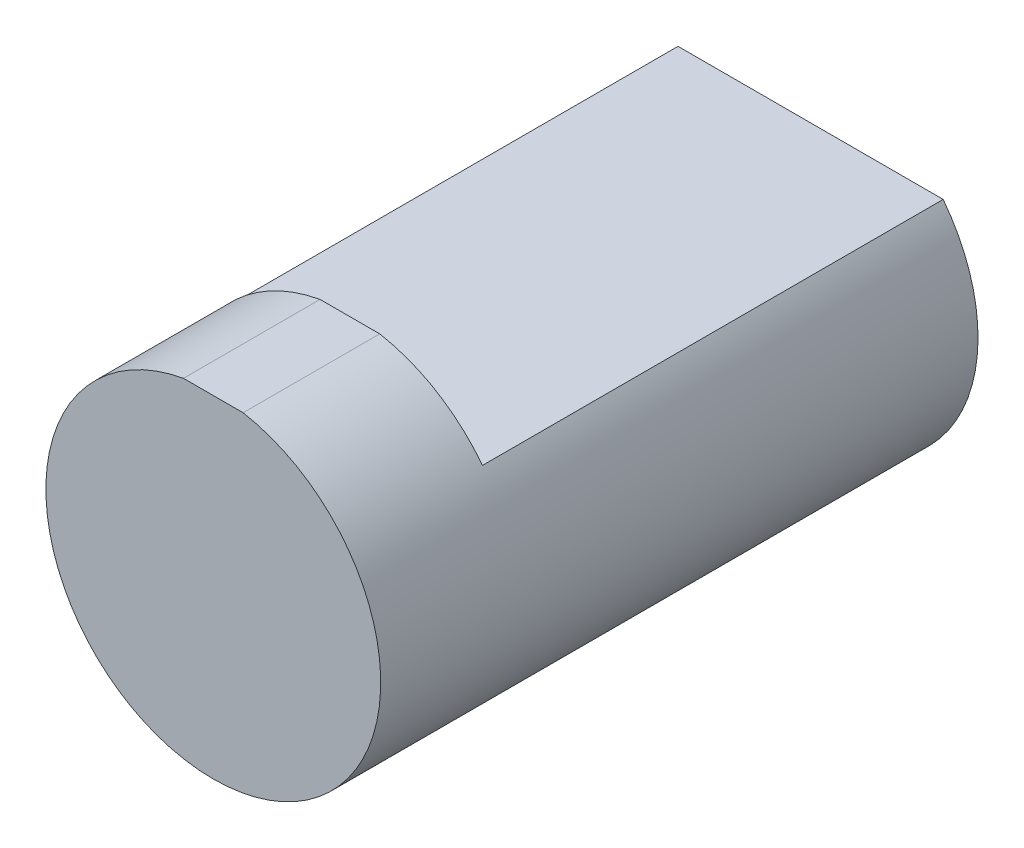
SolidWorks part; units mm, degrees
ref_plane "Front Plane" through (0, 0, 0) normal (0, 0, 1) x (1, 0, 0)
ref_plane "Top Plane" through (0, 0, 0) normal (0, 1, 0) x (1, 0, 0)
ref_plane "Right Plane" through (0, 0, 0) normal (1, 0, 0) x (0, 0, -1)
sketch "Sketch1" plane through (0, 0, 0) normal (0, 0, 1) x (1, 0, 0)
  circle A0 centre (0, 0) radius 62.5
  dimension "D2" = 125
extrude "Boss-Extrude3" add sketch "Sketch1" along normal blind 223
ref_plane "Plane1" through (0, 0, 0) normal (0, 0, -1) x (-1, 0, 0)
sketch "Sketch2" plane through (0, 0, 0) normal (0, 0, -1) x (-1, 0, 0)
  line L0 (-49.5, 38.1576) -> (49.5, 38.1576)
  circle A0 centre (0, 0) radius 62.5 construction
  dimension "D1" = 99
extrude "Cut-Extrude1" cut sketch "Sketch2" against normal blind 172 and the other way through all
ref_plane "Plane2" through (-62.5, 0, 0) normal (1, 0, 0) x (0, 0, -1)
sketch "Sketch3" plane through (-62.5, 0, 0) normal (1, 0, 0) x (0, 0, -1)
  line L0 (-223, 62.5) -> (-172, 62.5)
  line L1 (-172, 62.5) -> (-172, 61.5)
  line L2 (-172, 38.1576) -> (-172, 62.5) construction
  line L3 (-172, 61.5) -> (-223, 61.5)
  line L4 (-223, 62.5) -> (-223, -62.5) construction
  line L5 (-223, 61.5) -> (-223, 62.5)
  dimension "D1" = 1
extrude "Cut-Extrude2" cut sketch "Sketch3" along normal blind 174
